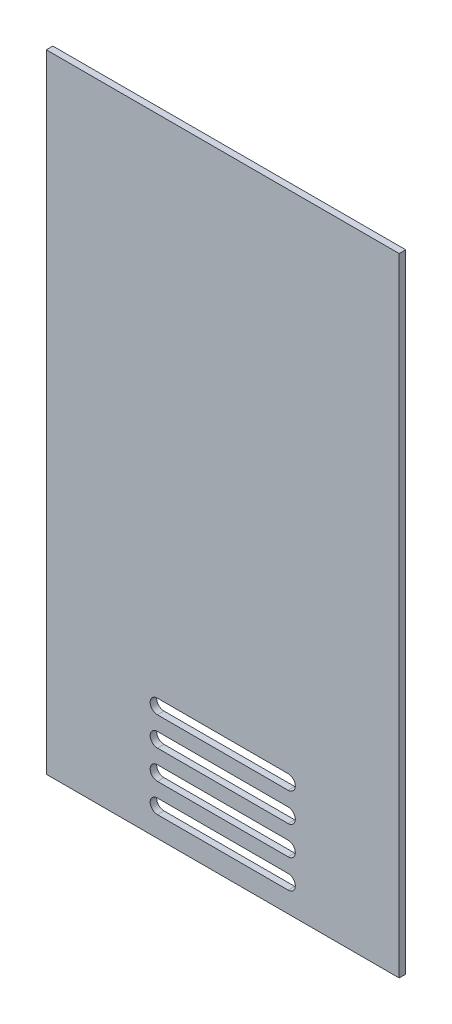
SolidWorks part; units mm, degrees
ref_plane "Front Plane" through (0, 0, 0) normal (0, 0, 1) x (1, 0, 0)
ref_plane "Top Plane" through (0, 0, 0) normal (0, 1, 0) x (1, 0, 0)
ref_plane "Right Plane" through (0, 0, 0) normal (1, 0, 0) x (0, 0, -1)
sketch "Sketch1" plane through (0, 0, 0) normal (0, 0, 1) x (1, 0, 0)
  line L1 (-113.4367, 87.7969) -> (58.0133, 87.7969)
  line L2 (-113.4367, 87.7969) -> (-113.4367, -217.0031)
  line L3 (-113.4367, -217.0031) -> (58.0133, -217.0031)
  line L4 (58.0133, 87.7969) -> (58.0133, -217.0031)
  dimension "D1" = 171.45
  dimension "D2" = 304.8
extrude "Boss-Extrude1" add sketch "Sketch1" along normal blind 3.175
sketch "Sketch2" plane through (0, 0, 3.175) normal (0, 0, 1) x (1, 0, 0)
  line L1 (-59.4617, -200.0031) -> (4.0383, -200.0031)
  line L3 (-59.4617, -207.0031) -> (4.0383, -207.0031)
  line L5 (-113.4367, -217.0031) -> (58.0133, -217.0031) construction
  line L6 (-59.4617, -186.0031) -> (4.0383, -186.0031)
  line L7 (-59.4617, -193.0031) -> (4.0383, -193.0031)
  line L8 (-59.4617, -172.0031) -> (4.0383, -172.0031)
  line L9 (-59.4617, -179.0031) -> (4.0383, -179.0031)
  line L10 (-59.4617, -158.0031) -> (4.0383, -158.0031)
  line L11 (-59.4617, -165.0031) -> (4.0383, -165.0031)
  arc A0 (-59.4617, -200.0031) -> (-59.4617, -207.0031) centre (-59.4617, -203.5031) ccw
  arc A1 (4.0383, -200.0031) -> (4.0383, -207.0031) centre (4.0383, -203.5031) cw
  arc A2 (-59.4617, -186.0031) -> (-59.4617, -193.0031) centre (-59.4617, -189.5031) ccw
  arc A3 (4.0383, -186.0031) -> (4.0383, -193.0031) centre (4.0383, -189.5031) cw
  arc A4 (-59.4617, -172.0031) -> (-59.4617, -179.0031) centre (-59.4617, -175.5031) ccw
  arc A5 (4.0383, -172.0031) -> (4.0383, -179.0031) centre (4.0383, -175.5031) cw
  arc A6 (-59.4617, -158.0031) -> (-59.4617, -165.0031) centre (-59.4617, -161.5031) ccw
  arc A7 (4.0383, -158.0031) -> (4.0383, -165.0031) centre (4.0383, -161.5031) cw
  dimension "D1" = 63.5
  dimension "D2" = 4
  dimension "D3" = 7
  dimension "D4" = 10
extrude "Cut-Extrude1" cut sketch "Sketch2" against normal blind 3.175
